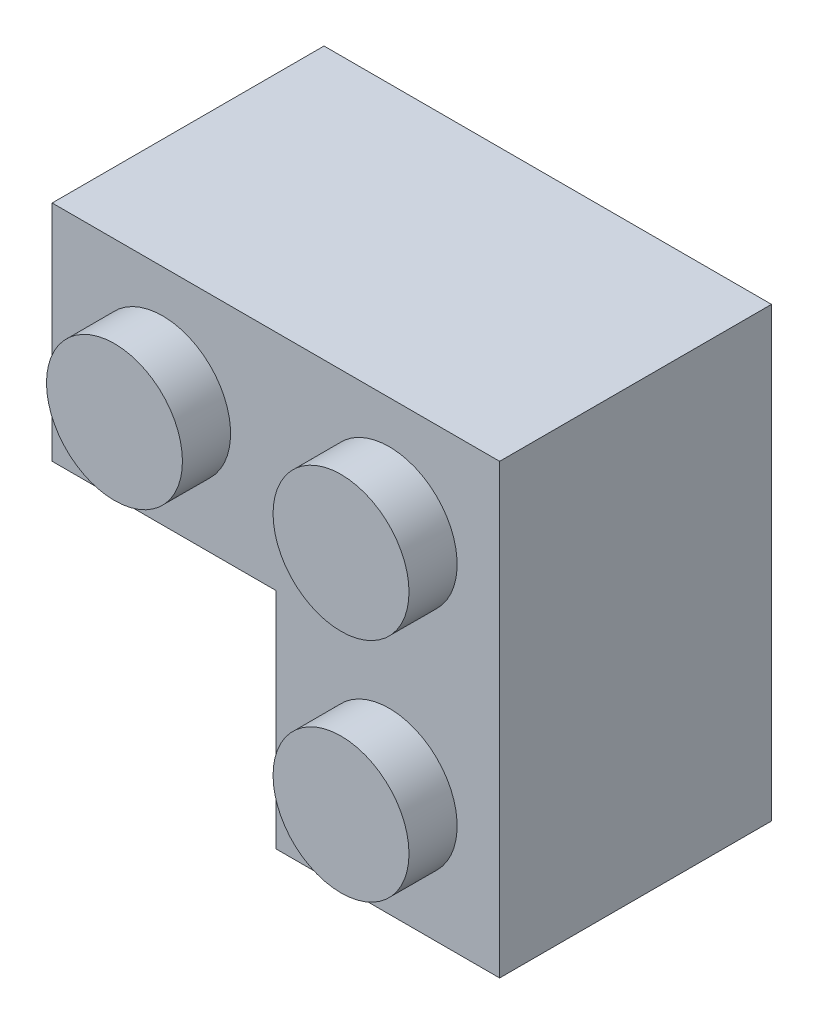
SolidWorks part; units mm, degrees
ref_plane "Спереди" through (0, 0, 0) normal (0, 0, 1) x (1, 0, 0)
ref_plane "Сверху" through (0, 0, 0) normal (0, 1, 0) x (1, 0, 0)
ref_plane "Справа" through (0, 0, 0) normal (1, 0, 0) x (0, 0, -1)
sketch "Эскиз1" plane through (0, 0, 0) normal (0, 0, 1) x (1, 0, 0)
  line L1 (7.9, 7.9) -> (-7.9, 7.9)
  line L2 (7.9, 7.9) -> (7.9, -7.9)
  line L3 (7.9, -7.9) -> (0, -7.9)
  line L4 (-7.9, 7.9) -> (-7.9, 0)
  line L5 (7.9, 7.9) -> (0, 0) construction
  line L6 (7.9, -7.9) -> (-7.9, 7.9) construction
  line L7 (0, 0) -> (-7.9, 0)
  line L8 (0, 0) -> (0, -7.9)
  point P0 (0, 0)
  dimension "D1" = 15.8
extrude "Бобышка-Вытянуть1" add sketch "Эскиз1" along normal blind 9.6
sketch "Эскиз2" plane through (0, 0, 9.6) normal (0, 0, 1) x (1, 0, 0)
  line L0 (7.9, 7.9) -> (-7.9, 7.9) construction
  line L1 (-7.9, 7.9) -> (-7.9, 0) construction
  line L2 (0, -7.9) -> (7.9, -7.9) construction
  line L3 (7.9, -7.9) -> (7.9, 7.9) construction
  circle A0 centre (-4, 4) radius 2.4
  circle A1 centre (4, 4) radius 2.4
  circle A2 centre (4, -4) radius 2.4
  dimension "D1" = 3.9
  dimension "D3" = 3.9
  dimension "D2" = 3.9
  dimension "D4" = 3.9
  dimension "D5" = 3.9
  dimension "D6" = 3.9
extrude "Бобышка-Вытянуть2" add sketch "Эскиз2" along normal blind 1.7
sketch "Эскиз3" plane through (0, 0, 0) normal (0, 0, -1) x (-1, 0, 0)
  line L0 (7.9, 7.9) -> (7.9, 0) construction
  line L1 (-7.9, 7.9) -> (7.9, 7.9) construction
  line L2 (-7.9, -7.9) -> (-7.9, 7.9) construction
  line L3 (0, -7.9) -> (-7.9, -7.9) construction
  circle A0 centre (4, 4) radius 2.5
  circle A1 centre (-4, 4) radius 2.5
  circle A2 centre (-4, -4) radius 2.5
  point P6 (0, 0)
  point P11 (-3.9596, 4)
  dimension "D1" = 3.9
  dimension "D2" = 3.9
  dimension "D3" = 3.9
  dimension "D4" = 3.9
  dimension "D5" = 3.9
  dimension "D6" = 3.9
extrude "Вырез-Вытянуть1" cut sketch "Эскиз3" against normal blind 1.8
